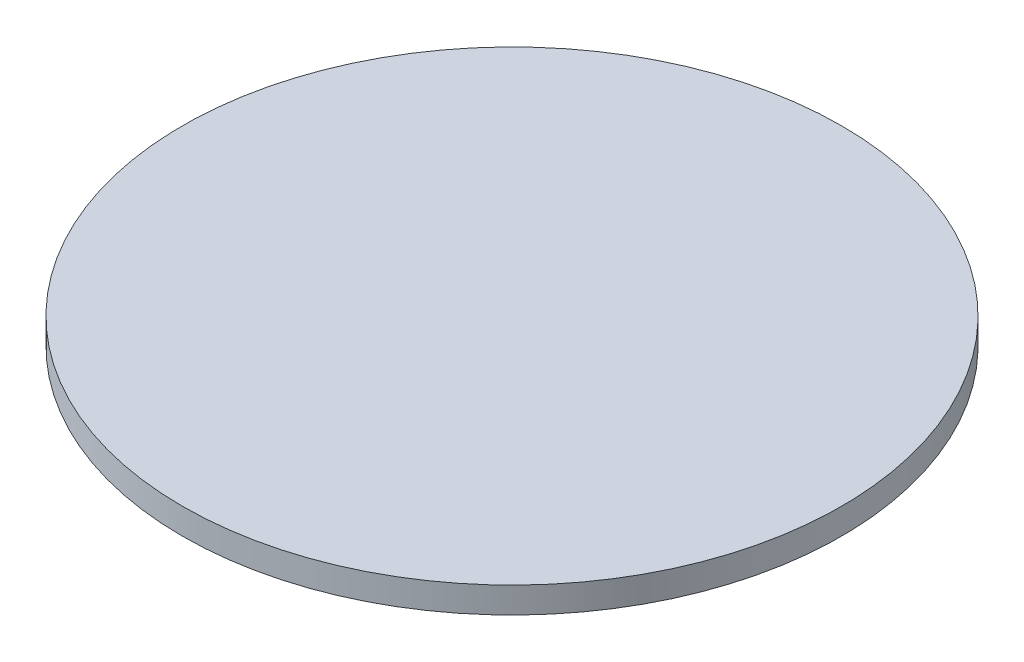
SolidWorks part; units mm, degrees
ref_plane "Front Plane" through (0, 0, 0) normal (0, 0, 1) x (1, 0, 0)
ref_plane "Top Plane" through (0, 0, 0) normal (0, 1, 0) x (1, 0, 0)
ref_plane "Right Plane" through (0, 0, 0) normal (1, 0, 0) x (0, 0, -1)
sketch "Reconstructed nominal axial profile" plane through (0, 0, 0) normal (0, 0, 1) x (1, 0, 0)
  line L0 (0, -500) -> (0, 50) construction
  line L1 (0, 0) -> (0, 2)
  line L2 (0, 2) -> (25.4, 2)
  line L3 (25.4, 2) -> (25.4, 0)
  line L4 (25.4, 0) -> (0, 0)
revolve "Native revolved geometry" add sketch "Reconstructed nominal axial profile" angle 360 about L0
